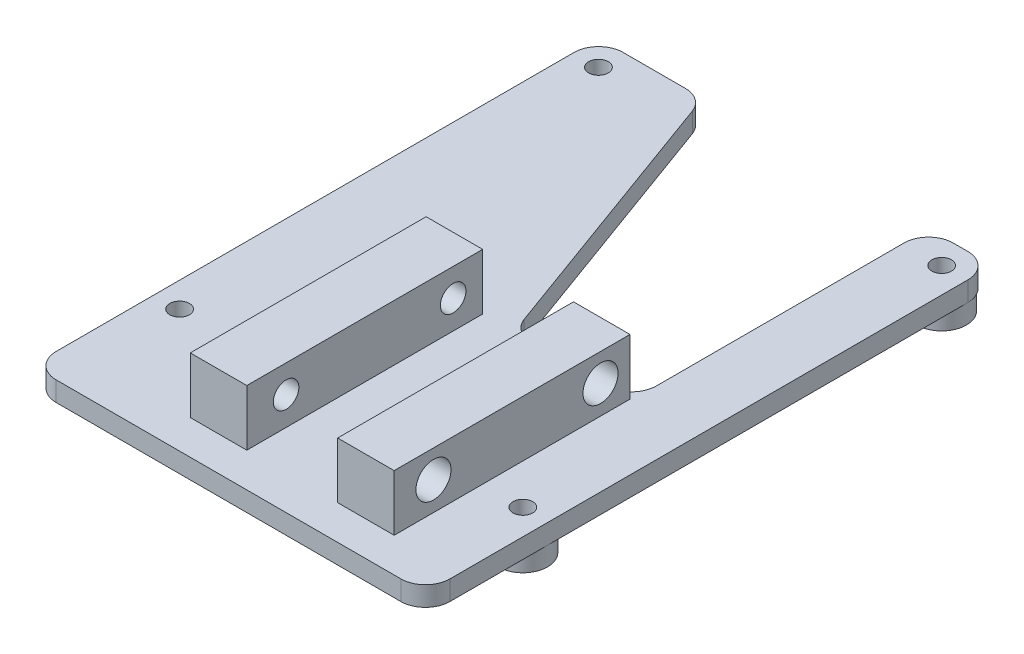
SolidWorks part; units mm, degrees
material "Onyx w/ CF"
ref_plane "Front Plane" through (0, 0, 0) normal (0, 0, 1) x (1, 0, 0)
ref_plane "Top Plane" through (0, 0, 0) normal (0, 1, 0) x (1, 0, 0)
ref_plane "Right Plane" through (0, 0, 0) normal (1, 0, 0) x (0, 0, -1)
sketch "Sketch1" plane through (0, 0, 0) normal (0, 1, 0) x (1, 0, 0)
  line L1 (-10.373, 12) -> (10.373, 12)
  line L2 (-10.373, 12) -> (-10.373, -12)
  line L3 (-10.373, -12) -> (10.373, -12)
  line L4 (10.373, 12) -> (10.373, -12)
  line L5 (-10.373, 12) -> (10.373, -12) construction
  line L6 (-10.373, -12) -> (10.373, 12) construction
  point P0 (0, 0)
  dimension "D1" = 20.746
  dimension "D2" = 24
extrude "Boss-Extrude1" add sketch "Sketch1" along normal blind 5.7
sketch "Sketch9" plane through (0, 0, 0) normal (0, -1, 0) x (1, 0, 0)
  line L0 (-10.373, 12) -> (10.373, 12) construction
  line L1 (4.623, -12) -> (-4.623, -12)
  line L2 (4.623, -12) -> (4.623, 12)
  line L3 (4.623, 12) -> (-4.623, 12)
  line L4 (-4.623, -12) -> (-4.623, 12)
  line L5 (4.623, -12) -> (-4.623, 12) construction
  line L6 (4.623, 12) -> (-4.623, -12) construction
  line L7 (10.373, -12) -> (-10.373, -12) construction
  line L8 (10.373, 12) -> (10.373, -12) construction
  point P0 (0, 0)
  dimension "D1" = 5.75
extrude "Cut-Extrude3" cut sketch "Sketch9" against normal through all
hole_wizard "9/64 (0.14063) Diameter Hole1" positions "Sketch6" profile "Sketch7" hole size "9/64" standard "ANSI Inch"
sketch "Sketch6" plane through (10.373, 0, 0) normal (1, 0, 0) x (0, 0, -1)
  line L4 (9, 2.9) -> (-8, 2.9) construction
  line L7 (-12, 5.7) -> (12, 5.7) construction
  line L9 (-12, 5.7) -> (-12, 0) construction
  line L10 (-8, 2.9) -> (9, 2.9) construction
  point P0 (9, 2.9)
  point P2 (-8, 2.9)
  dimension "D1" = 4
  dimension "D2" = 2.8
  dimension "D3" = 17
sketch "Sketch7" plane through (10.373, 2.9, -9) normal (0, 1, 0) x (0, 0, -1)
  line L0 (0, 0) -> (0, 6.8231)
  line L1 (0, 6.8231) -> (1.786, 5.75)
  line L2 (1.786, 5.75) -> (1.786, 0)
  line L5 (1.786, 0) -> (0, 0)
  line L10 (0, 6.8231) -> (-1.786, 5.75) construction
  line L11 (0, -6.35) -> (0, 107.95) construction
  dimension "Hole Dia." = 3.572
  dimension "Hole Depth" = 5.75
  dimension "Drill Angle" = 118
sketch "Sketch8" plane through (-10.373, 0, 0) normal (-1, 0, 0) x (0, 0, 1)
  line L0 (8, 2.9) -> (-9, 2.9) construction
  line L1 (-12, 5.7) -> (12, 5.7) construction
  line L3 (12, 5.7) -> (12, 0) construction
  circle A0 centre (8, 2.9) radius 1.3
  circle A1 centre (-9, 2.9) radius 1.3
  dimension "D1" = 2.8
  dimension "D4" = 2.6
  dimension "D2" = 17
  dimension "D3" = 4
extrude "Cut-Extrude2" cut sketch "Sketch8" against normal up to surface (5.75 mm away) up to face at (-4.623, 2.85, 0)
sketch "Sketch10" plane through (0, 0, 0) normal (0, -1, 0) x (1, 0, 0)
  line L0 (4.623, 12) -> (10.373, 12) construction
  line L1 (17.053, 15.5) -> (-23.027, 15.5)
  line L2 (17.053, 15.5) -> (17.053, -42.2)
  line L3 (17.053, -42.2) -> (-23.027, -42.2)
  line L4 (-23.027, 15.5) -> (-23.027, -42.2)
  line L5 (10.373, 12) -> (10.373, -12) construction
  dimension "D1" = 40.08
  dimension "D2" = 57.7
  dimension "D3" = 3.5
  dimension "D4" = 6.68
extrude "Boss-Extrude2" add sketch "Sketch10" along normal blind 2
sketch "Sketch11" plane through (0, -2, 0) normal (0, -1, 0) x (1, 0, 0)
  line L0 (-23.027, 15.5) -> (-23.027, -42.2) construction
  line L1 (17.053, 15.5) -> (-23.027, 15.5) construction
  line L2 (17.053, -42.2) -> (17.053, 15.5) construction
  line L3 (-23.027, -42.2) -> (17.053, -42.2) construction
  circle A0 centre (14.453, 2.985) radius 2.515
  circle A1 centre (-20.475, 2.985) radius 2.515
  circle A2 centre (14.45, -39.6362) radius 2.515
  circle A3 centre (-20.475, -39.6362) radius 2.515
  dimension "D1" = 5.03
  dimension "D2" = 2.6
  dimension "D3" = 2.552
  dimension "D4" = 2.5638
  dimension "D5" = 2.603
  dimension "D6" = 2.5638
  dimension "D7" = 2.552
  dimension "D8" = 12.515
extrude "Boss-Extrude3" add sketch "Sketch11" along normal blind 2
sketch "Sketch12" plane through (0, -4, 0) normal (0, -1, 0) x (1, 0, 0)
  circle A0 centre (14.453, 2.985) radius 1
  circle A1 centre (-20.475, 2.985) radius 1
  circle A2 centre (-20.475, -39.6362) radius 1
  circle A3 centre (14.45, -39.6362) radius 1
  circle A4 centre (-20.475, -39.6362) radius 2.515 construction
  circle A5 centre (14.45, -39.6362) radius 2.515 construction
  circle A6 centre (14.453, 2.985) radius 2.515 construction
  circle A7 centre (-20.475, 2.985) radius 2.515 construction
  dimension "D1" = 2
extrude "Cut-Extrude4" cut sketch "Sketch12" against normal through all
fillet "Fillet2" radius 2.5 4 edges at (17.053, -1, -42.2) (-23.027, -1, -42.2) (-23.027, -1, 15.5) (17.053, -1, 15.5)
sketch "Sketch14" plane through (0, 0, 0) normal (0, 1, 0) x (1, 0, 0)
  line L4 (10.553, 42.2) -> (10.553, 12)
  line L5 (10.553, 12) -> (-1.447, 12)
  line L6 (-1.447, 12) -> (-12.4389, 42.2)
  line L7 (-20.527, 42.2) -> (14.553, 42.2) construction
  line L8 (10.373, 12) -> (4.623, 12) construction
  line L9 (-12.4389, 42.2) -> (10.553, 42.2)
  dimension "D1" = 4
  dimension "D2" = 12
  dimension "D3" = 20
extrude "Cut-Extrude5" cut sketch "Sketch14" against normal through all
fillet "Fillet3" radius 2.5 4 edges at (10.553, -1, -12) (-1.447, -1, -12) (10.553, -1, -42.2) (-12.4389, -1, -42.2)
sketch "Sketch15" plane through (0, 5.7, 0) normal (0, 1, 0) x (1, 0, 0)
  line L0 (8.053, 12) -> (10.373, 12)
  line L1 (8.053, 12) -> (4.623, 12) construction
  line L2 (10.373, -12) -> (10.373, 13.5685) construction
  line L3 (10.373, 12) -> (10.373, 13.5685)
  arc A0 (8.053, 12) -> (10.373, 13.5685) centre (8.053, 14.5) ccw construction
  arc A1 (10.373, 13.5685) -> (8.053, 12) centre (8.053, 14.5) cw
extrude "Cut-Extrude6" cut sketch "Sketch15" against normal up to surface (5.7 mm away) up to face at (0.6321, 0, -16.5094)
